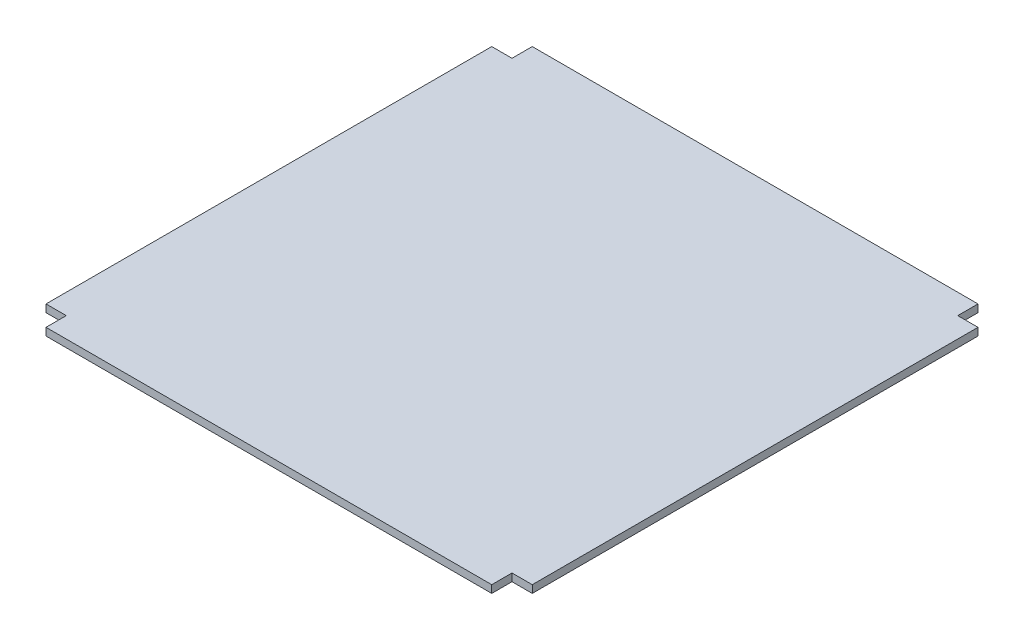
SolidWorks part; units mm, degrees
ref_plane "Front Plane" through (0, 0, 0) normal (0, 0, 1) x (1, 0, 0)
ref_plane "Top Plane" through (0, 0, 0) normal (0, 1, 0) x (1, 0, 0)
ref_plane "Right Plane" through (0, 0, 0) normal (1, 0, 0) x (0, 0, -1)
sketch "Sketch1" plane through (0, 0, 0) normal (0, 1, 0) x (1, 0, 0)
  line L1 (-609.6, -609.6) -> (609.6, -609.6)
  line L2 (-609.6, -609.6) -> (-609.6, 609.6)
  line L3 (-609.6, 609.6) -> (609.6, 609.6)
  line L4 (609.6, -609.6) -> (609.6, 609.6)
  line L5 (-609.6, -609.6) -> (609.6, 609.6) construction
  line L6 (-609.6, 609.6) -> (609.6, -609.6) construction
  point P0 (0, 0)
  dimension "D2" = 1219.2
  dimension "D1" = 1219.2
extrude "Boss-Extrude1" add sketch "Sketch1" along normal mid plane 19.05
sketch "Sketch2" plane through (0, 9.525, 0) normal (0, 1, 0) x (1, 0, 0)
  line L0 (0, 609.6) -> (0, -609.6) construction
  line L1 (-609.6, 609.6) -> (-558.8, 609.6)
  line L2 (-609.6, 609.6) -> (-609.6, 558.8)
  line L3 (-609.6, 558.8) -> (-558.8, 558.8)
  line L4 (-558.8, 609.6) -> (-558.8, 558.8)
  line L5 (609.6, 609.6) -> (-609.6, 609.6) construction
  line L6 (-609.6, -609.6) -> (609.6, -609.6) construction
  line L7 (609.6, 0) -> (-609.6, 0) construction
  line L8 (609.6, -609.6) -> (609.6, 609.6) construction
  line L9 (-609.6, 609.6) -> (-609.6, -609.6) construction
  line L10 (558.8, 609.6) -> (558.8, 558.8)
  line L11 (609.6, 558.8) -> (558.8, 558.8)
  line L12 (609.6, 609.6) -> (609.6, 558.8)
  line L13 (609.6, 609.6) -> (558.8, 609.6)
  line L14 (609.6, -609.6) -> (558.8, -609.6)
  line L15 (609.6, -609.6) -> (609.6, -558.8)
  line L16 (609.6, -558.8) -> (558.8, -558.8)
  line L17 (558.8, -609.6) -> (558.8, -558.8)
  line L18 (-558.8, -609.6) -> (-558.8, -558.8)
  line L19 (-609.6, -558.8) -> (-558.8, -558.8)
  line L20 (-609.6, -609.6) -> (-609.6, -558.8)
  line L21 (-609.6, -609.6) -> (-558.8, -609.6)
  dimension "D1" = 50.8
extrude "Cut-Extrude1" cut sketch "Sketch2" against normal through all
equation "\"width\"= 48in"
equation "\"length\"= 48in"
equation "\"square tubing width\"= 2in"
equation "\"D1@Sketch2\"=\"square tubing width\""
equation "\"D1@Sketch1\"=\"width\""
equation "\"D2@Sketch1\"=\"length\""
